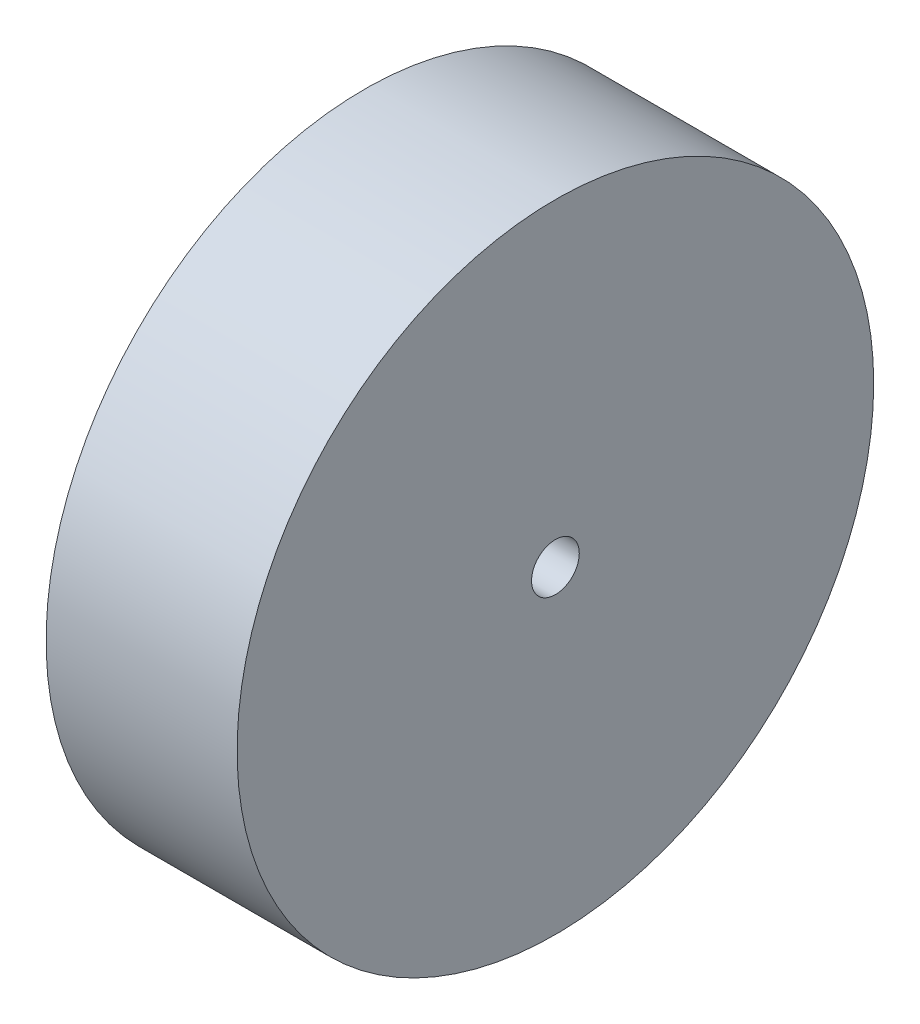
SolidWorks part; units mm, degrees
material "3.1645 (EN AW-2007)"
ref_plane "Plano frontal" through (0, 0, 0) normal (0, 0, 1) x (1, 0, 0)
ref_plane "Plano superior" through (0, 0, 0) normal (0, 1, 0) x (1, 0, 0)
ref_plane "Plano direito" through (0, 0, 0) normal (1, 0, 0) x (0, 0, -1)
sketch "Esboço3" plane through (0, 0, 0) normal (0, 0, 1) x (1, 0, 0)
  line L0 (0, 0) -> (-50.7324, 0) construction
  line L1 (0, 10) -> (0, 0.75)
  line L2 (-1, 9) -> (-1, 2)
  line L3 (-6, 2) -> (-6, 0)
  line L4 (-1, 2) -> (-6, 2)
  line L5 (-6, 0) -> (-5, 0)
  line L6 (-5, 0.75) -> (0, 0.75)
  line L7 (-1, 9) -> (-6, 9)
  line L8 (-6, 9) -> (-6, 10)
  line L9 (-6, 10) -> (0, 10)
  line L10 (-5, 0) -> (-5, 0.75)
  dimension "D1" = 0.75
  dimension "D2" = 10
  dimension "D3" = 1
  dimension "D4" = 5
  dimension "D5" = 2
  dimension "D6" = 1
  dimension "D7" = 6
  dimension "D8" = 1
revolve "Revolução1" add sketch "Esboço3" angle 360 about L0
ref_plane "Plano1" through (0, 2, 0) normal (0, 1, 0) x (1, 0, 0)
hole_wizard "Broca de rosquear para tarraxa de M2.2x0.451" positions "3DSketch6" profile "Esboço11" hole size "M2.2x0.45" standard "DIN"
sketch3d "3DSketch6"
  point P0 (-6, 5, 0)
  dimension "D1" = 3
sketch "Esboço11" plane through (-6, 5, 0) normal (1, 0, 0) x (0, 0, 1)
  line L0 (0, 0) -> (0, 3)
  line L1 (0, 3) -> (0.875, 3)
  line L2 (0.875, 3) -> (0.875, 0)
  line L5 (0.875, 0) -> (0, 0)
  line L11 (0, -6.35) -> (0, 107.95) construction
  dimension "Thru Hole Dia." = 1.75
  dimension "Thru Hole Depth" = 3
